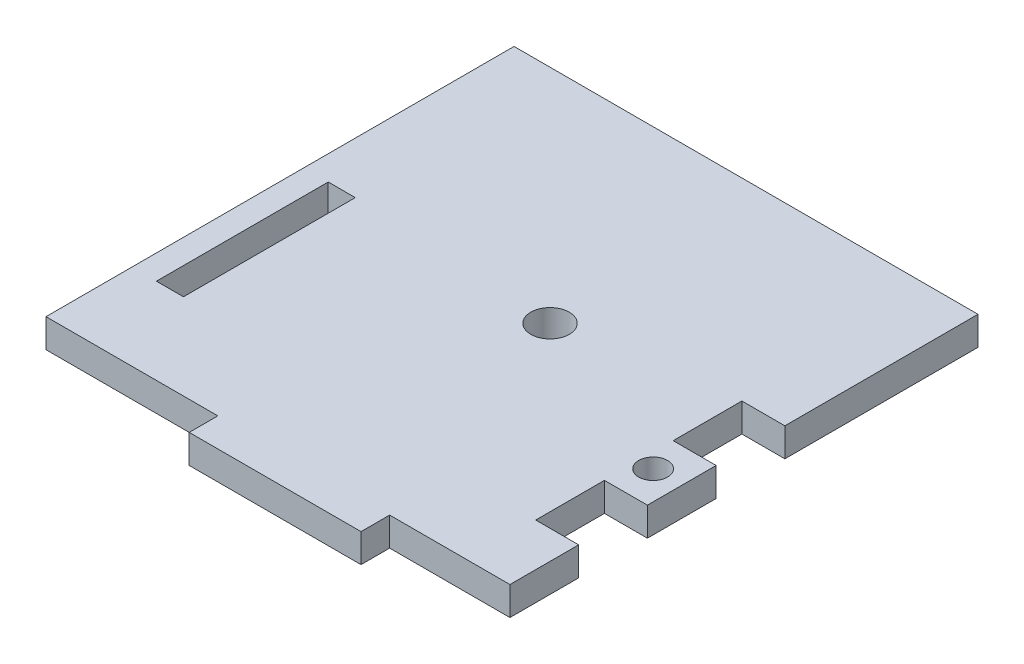
SolidWorks part; units mm, degrees
ref_plane "Front Plane" through (0, 0, 0) normal (0, 0, 1) x (1, 0, 0)
ref_plane "Top Plane" through (0, 0, 0) normal (0, 1, 0) x (1, 0, 0)
ref_plane "Right Plane" through (0, 0, 0) normal (1, 0, 0) x (0, 0, -1)
sketch "Sketch1" plane through (0, 0, 0) normal (0, 1, 0) x (1, 0, 0)
  line L0 (0, 0) -> (19.05, 0)
  line L1 (19.05, 0) -> (19.05, -3.175)
  line L2 (19.05, -3.175) -> (38.1, -3.175)
  line L3 (38.1, -3.175) -> (38.1, 0)
  line L4 (38.1, 0) -> (51.435, 0)
  line L5 (51.435, 0) -> (51.435, 7.62)
  line L6 (0, 51.8922) -> (0, 0)
  line L10 (51.435, 51.8922) -> (0, 51.8922)
  line L16 (51.435, 15.24) -> (51.435, 22.86)
  line L17 (46.6725, 30.48) -> (51.435, 30.48)
  line L18 (46.6725, 30.48) -> (46.6725, 22.86)
  line L19 (46.6725, 22.86) -> (51.435, 22.86)
  line L20 (51.435, 30.48) -> (51.435, 51.8922)
  line L21 (46.6725, 15.24) -> (51.435, 15.24)
  line L22 (46.6725, 15.24) -> (46.6725, 7.62)
  line L23 (46.6725, 7.62) -> (51.435, 7.62)
  dimension "D2" = 13.335
  dimension "D3" = 19.05
  dimension "D4" = 51.435
  dimension "D5" = 51.8922
  dimension "D7" = 4.7625
  dimension "D8" = 7.62
  dimension "D9" = 7.62
  dimension "D10" = 7.62
  dimension "D11" = 7.62
extrude "Boss-Extrude1" add sketch "Sketch1" along normal blind 3.175
hole_wizard "M3 Clearance Hole1" positions "Sketch3" profile "Sketch2" hole size "M3" standard "ANSI Metric" end condition through all
sketch "Sketch3" plane through (0, 3.175, 0) normal (0, 1, 0) x (1, 0, 0)
  line L3 (48.26, 22.86) -> (48.26, 15.24) construction
  line L4 (51.435, 22.86) -> (46.6725, 22.86) construction
  line L5 (46.6725, 15.24) -> (51.435, 15.24) construction
  line L8 (46.6725, 22.86) -> (46.6725, 30.48) construction
  point P0 (48.26, 19.05)
  point P21 (48.26, 19.05)
  dimension "D1" = 1.5875
sketch "Sketch2" plane through (48.26, 3.175, -19.05) normal (1, 0, 0) x (0, 0, 1)
  line L0 (0, 0) -> (0, 3.175)
  line L1 (0, 3.175) -> (1.6, 3.175)
  line L2 (1.6, 3.175) -> (1.6, 0)
  line L5 (1.6, 0) -> (0, 0)
  line L11 (0, -6.35) -> (0, 107.95) construction
  dimension "Thru Hole Dia." = 3.2
  dimension "Thru Hole Depth" = 3.175
sketch "Sketch4" plane through (0, 3.175, 0) normal (0, 1, 0) x (1, 0, 0)
  line L0 (19.05, -3.175) -> (38.1, -3.175) construction
  line L1 (28.575, 27.305) -> (28.575, -3.175) construction
  circle A0 centre (28.575, 27.305) radius 2.1336
  dimension "D1" = 4.2672
  dimension "D2" = 30.48
extrude "Cut-Extrude1" cut sketch "Sketch4" against normal through all
sketch "Sketch5" plane through (0, 3.175, 0) normal (0, 1, 0) x (1, 0, 0)
  line L0 (0, 0) -> (19.05, 0) construction
  line L1 (2.715, 28.575) -> (5.715, 28.575)
  line L2 (2.715, 28.575) -> (2.715, 9.525)
  line L3 (2.715, 9.525) -> (5.715, 9.525)
  line L4 (5.715, 28.575) -> (5.715, 9.525)
  line L6 (51.435, 0) -> (51.435, 7.62) construction
  dimension "D1" = 3
  dimension "D2" = 9.525
  dimension "D3" = 19.05
  dimension "D4" = 45.72
extrude "Cut-Extrude2" cut sketch "Sketch5" against normal through all
